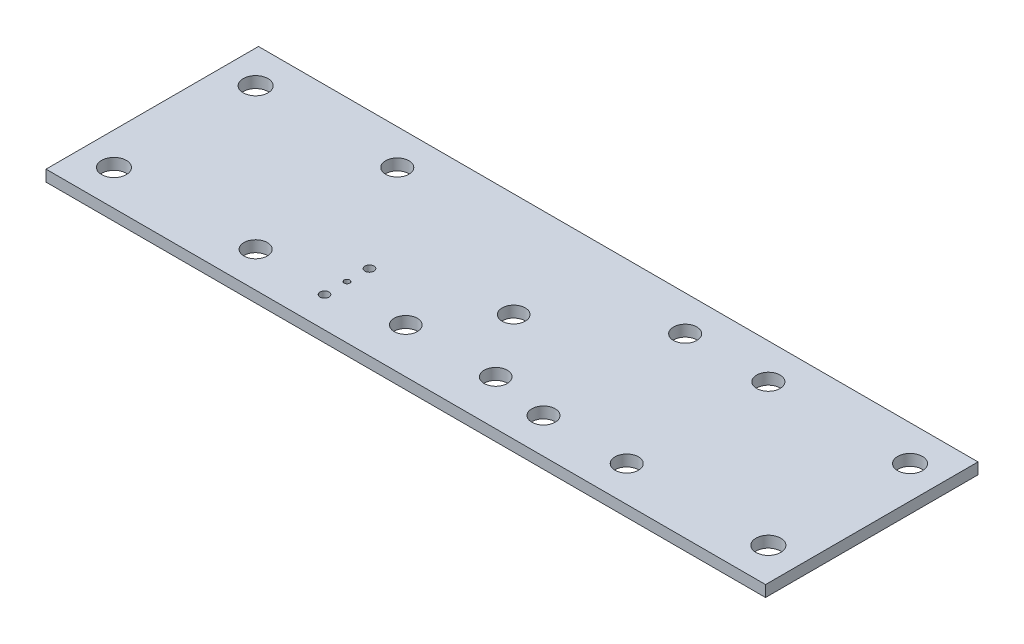
SolidWorks part; units mm, degrees
ref_plane "Front Plane" through (0, 0, 0) normal (0, 0, 1) x (1, 0, 0)
ref_plane "Top Plane" through (0, 0, 0) normal (0, 1, 0) x (1, 0, 0)
ref_plane "Right Plane" through (0, 0, 0) normal (1, 0, 0) x (0, 0, -1)
sketch "Sketch1" plane through (0, 0, 0) normal (0, 1, 0) x (1, 0, 0)
  line L0 (0, 0) -> (76.4014, 0) construction
  line L1 (-101.6, 30) -> (101.6, 30)
  line L2 (-101.6, 30) -> (-101.6, -30)
  line L3 (-101.6, -30) -> (101.6, -30)
  line L4 (101.6, 30) -> (101.6, -30)
  line L5 (-101.6, 30) -> (101.6, -30) construction
  line L6 (-101.6, -30) -> (101.6, 30) construction
  line L7 (0, 0) -> (0, 23.5578) construction
  circle A0 centre (-52.4, 20) radius 3.3
  circle A1 centre (-92.4, -20) radius 3.5
  circle A2 centre (-52.4, -20) radius 3.3
  circle A3 centre (92.4, 20) radius 3.5
  circle A4 centre (-92.4, 20) radius 3.5
  circle A5 centre (52.4, -20) radius 3.3
  circle A6 centre (92.4, -20) radius 3.5
  circle A7 centre (52.4, 20) radius 3.3
  point P0 (0, 0)
  dimension "D1" = 6.6
  dimension "D4" = 7
  dimension "D2" = 40
  dimension "D5" = 40
  dimension "D6" = 60
  dimension "D7" = 9.2
  dimension "D8" = 203.2
extrude "Boss-Extrude1" add sketch "Sketch1" along normal blind 3.175
sketch "Sketch2" plane through (0, 3.175, 0) normal (0, 1, 0) x (1, 0, 0)
  line L0 (12.7, -17.3) -> (-12.7, -17.3) construction
  line L1 (-101.6, -30) -> (101.6, -30) construction
  circle A0 centre (-12.7, -17.3) radius 3.2639
  circle A1 centre (12.7, -17.3) radius 3.2639
  circle A2 centre (0, 0.48) radius 3.2639
  point P6 (0, -17.3)
  dimension "D1" = 12.7
  dimension "D2" = 6.5278
  dimension "D3" = 25.4
  dimension "D4" = 17.78
extrude "1/4-20 for Nut Bracket" cut sketch "Sketch2" against normal through all
sketch "Sketch3" plane through (0, 3.175, 0) normal (0, 1, 0) x (1, 0, 0)
  line L0 (-101.6, -30) -> (101.6, -30) construction
  line L2 (-101.6, 30) -> (-101.6, -30) construction
  circle A0 centre (-31.6, -15) radius 0.7937
  circle A1 centre (-31.6, -8.65) radius 1.27
  circle A2 centre (-31.6, -21.35) radius 1.27
  dimension "D1" = 1.5875
  dimension "D3" = 70
  dimension "D4" = 2.54
  dimension "D2" = 15
  dimension "D5" = 6.35
  dimension "D6" = 6.35
extrude "Wire Holder" cut sketch "Sketch3" against normal through all
sketch "Sketch4" plane through (0, 3.175, 0) normal (0, 1, 0) x (1, 0, 0)
  circle A0 centre (28.9, -20) radius 3.3
  circle A1 centre (28.9, 20) radius 3.3
  circle A2 centre (52.4, 20) radius 3.3 construction
  point P4 (92.4, -20)
  point P6 (92.4, 20)
  dimension "D1" = 63.5
extrude "Cut-Extrude1" cut sketch "Sketch4" against normal through all
